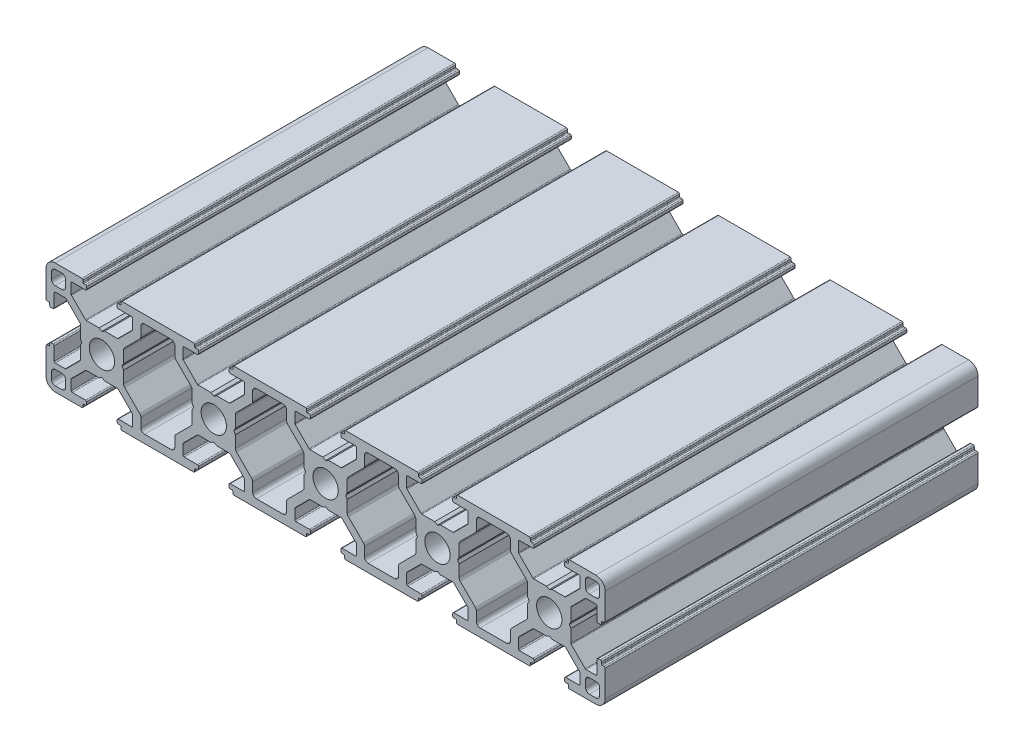
SolidWorks part; units mm, degrees
ref_plane "前视基准面" through (0, 0, 0) normal (0, 0, 1) x (1, 0, 0)
ref_plane "上视基准面" through (0, 0, 0) normal (0, 1, 0) x (1, 0, 0)
ref_plane "右视基准面" through (0, 0, 0) normal (1, 0, 0) x (0, 0, -1)
sketch "草图1" plane through (0, 0, 0) normal (0, 0, 1) x (1, 0, 0)
  line B0 (25.8114, -5.8) -> (29.25, -5.8)
  line B1 (29.25, -5.8) -> (30, -5.367)
  line B2 (30, -5.367) -> (30.75, -5.8)
  line B3 (30.75, -5.8) -> (34.1886, -5.8)
  line B4 (34.4007, -5.8879) -> (38.1622, -9.651)
  line B5 (38.25, -9.8631) -> (38.25, -12.5)
  line B6 (37.95, -12.8) -> (34.4, -12.8)
  line B7 (34.1, -13.1) -> (34.1, -13.7)
  line B8 (34.4, -14) -> (34.9, -14)
  line B9 (35.1, -14.2) -> (35.1, -14.7)
  line B10 (35.4, -15) -> (54.6, -15)
  line B11 (54.9, -14.7) -> (54.9, -14.2)
  line B12 (55.1, -14) -> (55.6, -14)
  line B13 (55.9, -13.7) -> (55.9, -13.1)
  line B14 (55.6, -12.8) -> (52.05, -12.8)
  line B15 (51.75, -12.5) -> (51.75, -9.8631)
  line B16 (51.8378, -9.651) -> (55.5993, -5.8879)
  line B17 (55.8114, -5.8) -> (59.25, -5.8)
  line B18 (59.25, -5.8) -> (60, -5.367)
  line B19 (60, -5.367) -> (60.75, -5.8)
  line B20 (60.75, -5.8) -> (64.1886, -5.8)
  line B21 (64.4007, -5.8879) -> (68.1622, -9.651)
  line B22 (68.25, -9.8631) -> (68.25, -12.5)
  line B23 (67.95, -12.8) -> (64.4, -12.8)
  line B24 (64.1, -13.1) -> (64.1, -13.7)
  line B25 (64.4, -14) -> (64.9, -14)
  line B26 (65.1, -14.2) -> (65.1, -14.7)
  line B27 (65.4, -15) -> (84.6, -15)
  line B28 (84.9, -14.7) -> (84.9, -14.2)
  line B29 (85.1, -14) -> (85.6, -14)
  line B30 (85.9, -13.7) -> (85.9, -13.1)
  line B31 (85.6, -12.8) -> (82.05, -12.8)
  line B32 (81.75, -12.5) -> (81.75, -9.8631)
  line B33 (81.8378, -9.651) -> (85.5993, -5.8879)
  line B34 (85.8114, -5.8) -> (89.25, -5.8)
  line B35 (89.25, -5.8) -> (90, -5.367)
  line B36 (90, -5.367) -> (90.75, -5.8)
  line B37 (90.75, -5.8) -> (94.1886, -5.8)
  line B38 (94.4007, -5.8879) -> (98.1622, -9.651)
  line B39 (98.25, -9.8631) -> (98.25, -12.5)
  line B40 (97.95, -12.8) -> (94.4, -12.8)
  line B41 (94.1, -13.1) -> (94.1, -13.7)
  line B42 (94.4, -14) -> (94.9, -14)
  line B43 (95.1, -14.2) -> (95.1, -14.7)
  line B44 (95.4, -15) -> (114.6, -15)
  line B45 (114.9, -14.7) -> (114.9, -14.2)
  line B46 (115.1, -14) -> (115.6, -14)
  line B47 (115.9, -13.7) -> (115.9, -13.1)
  line B48 (115.6, -12.8) -> (112.05, -12.8)
  line B49 (111.75, -12.5) -> (111.75, -9.8631)
  line B50 (111.8378, -9.651) -> (115.5993, -5.8879)
  line B51 (115.8114, -5.8) -> (119.25, -5.8)
  line B52 (119.25, -5.8) -> (120, -5.367)
  line B53 (120, -5.367) -> (120.75, -5.8)
  line B54 (120.75, -5.8) -> (124.1886, -5.8)
  line B55 (124.4007, -5.8879) -> (128.1622, -9.651)
  line B56 (128.25, -9.8631) -> (128.25, -12.5)
  line B57 (127.95, -12.8) -> (124.4, -12.8)
  line B58 (124.1, -13.1) -> (124.1, -13.7)
  line B59 (124.4, -14) -> (124.9, -14)
  line B60 (125.1, -14.2) -> (125.1, -14.7)
  line B61 (125.4, -15) -> (132.5, -15)
  line B62 (135, -12.5) -> (135, -5.4)
  line B63 (134.7, -5.1) -> (134.2, -5.1)
  line B64 (134, -4.9) -> (134, -4.4)
  line B65 (133.7, -4.1) -> (133.1, -4.1)
  line B66 (132.8, -4.4) -> (132.8, -7.95)
  line B67 (132.5, -8.25) -> (129.8553, -8.25)
  line B68 (129.6431, -8.1621) -> (125.8878, -4.4051)
  line B69 (125.8, -4.1931) -> (125.8, -0.75)
  line B70 (125.8, -0.75) -> (125.367, 0)
  line B71 (125.367, 0) -> (125.8, 0.75)
  line B72 (125.8, 0.75) -> (125.8, 4.1931)
  line B73 (125.8878, 4.4051) -> (129.6431, 8.1621)
  line B74 (129.8553, 8.25) -> (132.5, 8.25)
  line B75 (132.8, 7.95) -> (132.8, 4.4)
  line B76 (133.1, 4.1) -> (133.7, 4.1)
  line B77 (134, 4.4) -> (134, 4.9)
  line B78 (134.2, 5.1) -> (134.7, 5.1)
  line B79 (135, 5.4) -> (135, 12.5)
  line B80 (132.5, 15) -> (125.4, 15)
  line B81 (125.1, 14.7) -> (125.1, 14.2)
  line B82 (124.9, 14) -> (124.4, 14)
  line B83 (124.1, 13.7) -> (124.1, 13.1)
  line B84 (124.4, 12.8) -> (127.95, 12.8)
  line B85 (128.25, 12.5) -> (128.25, 9.8631)
  line B86 (128.1622, 9.651) -> (124.4007, 5.8879)
  line B87 (124.1886, 5.8) -> (120.75, 5.8)
  line B88 (120.75, 5.8) -> (120, 5.367)
  line B89 (120, 5.367) -> (119.25, 5.8)
  line B90 (119.25, 5.8) -> (115.8114, 5.8)
  line B91 (115.5993, 5.8879) -> (111.8378, 9.651)
  line B92 (111.75, 9.8631) -> (111.75, 12.5)
  line B93 (112.05, 12.8) -> (115.6, 12.8)
  line B94 (115.9, 13.1) -> (115.9, 13.7)
  line B95 (115.6, 14) -> (115.1, 14)
  line B96 (114.9, 14.2) -> (114.9, 14.7)
  line B97 (114.6, 15) -> (95.4, 15)
  line B98 (95.1, 14.7) -> (95.1, 14.2)
  line B99 (94.9, 14) -> (94.4, 14)
  line B100 (94.1, 13.7) -> (94.1, 13.1)
  line B101 (94.4, 12.8) -> (97.95, 12.8)
  line B102 (98.25, 12.5) -> (98.25, 9.8631)
  line B103 (98.1622, 9.651) -> (94.4007, 5.8879)
  line B104 (94.1886, 5.8) -> (90.75, 5.8)
  line B105 (90.75, 5.8) -> (90, 5.367)
  line B106 (90, 5.367) -> (89.25, 5.8)
  line B107 (89.25, 5.8) -> (85.8114, 5.8)
  line B108 (85.5993, 5.8879) -> (81.8378, 9.651)
  line B109 (81.75, 9.8631) -> (81.75, 12.5)
  line B110 (82.05, 12.8) -> (85.6, 12.8)
  line B111 (85.9, 13.1) -> (85.9, 13.7)
  line B112 (85.6, 14) -> (85.1, 14)
  line B113 (84.9, 14.2) -> (84.9, 14.7)
  line B114 (84.6, 15) -> (65.4, 15)
  line B115 (65.1, 14.7) -> (65.1, 14.2)
  line B116 (64.9, 14) -> (64.4, 14)
  line B117 (64.1, 13.7) -> (64.1, 13.1)
  line B118 (64.4, 12.8) -> (67.95, 12.8)
  line B119 (68.25, 12.5) -> (68.25, 9.8631)
  line B120 (68.1622, 9.651) -> (64.4007, 5.8879)
  line B121 (64.1886, 5.8) -> (60.75, 5.8)
  line B122 (60.75, 5.8) -> (60, 5.367)
  line B123 (60, 5.367) -> (59.25, 5.8)
  line B124 (59.25, 5.8) -> (55.8114, 5.8)
  line B125 (55.5993, 5.8879) -> (51.8378, 9.651)
  line B126 (51.75, 9.8631) -> (51.75, 12.5)
  line B127 (52.05, 12.8) -> (55.6, 12.8)
  line B128 (55.9, 13.1) -> (55.9, 13.7)
  line B129 (55.6, 14) -> (55.1, 14)
  line B130 (54.9, 14.2) -> (54.9, 14.7)
  line B131 (54.6, 15) -> (35.4, 15)
  line B132 (35.1, 14.7) -> (35.1, 14.2)
  line B133 (34.9, 14) -> (34.4, 14)
  line B134 (34.1, 13.7) -> (34.1, 13.1)
  line B135 (34.4, 12.8) -> (37.95, 12.8)
  line B136 (38.25, 12.5) -> (38.25, 9.8631)
  line B137 (38.1622, 9.651) -> (34.4007, 5.8879)
  line B138 (34.1886, 5.8) -> (30.75, 5.8)
  line B139 (30.75, 5.8) -> (30, 5.367)
  line B140 (30, 5.367) -> (29.25, 5.8)
  line B141 (29.25, 5.8) -> (25.8114, 5.8)
  line B142 (25.5993, 5.8879) -> (21.8378, 9.651)
  line B143 (21.75, 9.8631) -> (21.75, 12.5)
  line B144 (22.05, 12.8) -> (25.6, 12.8)
  line B145 (25.9, 13.1) -> (25.9, 13.7)
  line B146 (25.6, 14) -> (25.1, 14)
  line B147 (24.9, 14.2) -> (24.9, 14.7)
  line B148 (24.6, 15) -> (5.4, 15)
  line B149 (5.1, 14.7) -> (5.1, 14.2)
  line B150 (4.9, 14) -> (4.4, 14)
  line B151 (4.1, 13.7) -> (4.1, 13.1)
  line B152 (4.4, 12.8) -> (7.95, 12.8)
  line B153 (8.25, 12.5) -> (8.25, 9.8631)
  line B154 (8.1622, 9.651) -> (4.4007, 5.8879)
  line B155 (4.1886, 5.8) -> (0.75, 5.8)
  line B156 (0.75, 5.8) -> (0, 5.367)
  line B157 (0, 5.367) -> (-0.75, 5.8)
  line B158 (-0.75, 5.8) -> (-4.1886, 5.8)
  line B159 (-4.4007, 5.8879) -> (-8.1622, 9.651)
  line B160 (-8.25, 9.8631) -> (-8.25, 12.5)
  line B161 (-7.95, 12.8) -> (-4.4, 12.8)
  line B162 (-4.1, 13.1) -> (-4.1, 13.7)
  line B163 (-4.4, 14) -> (-4.9, 14)
  line B164 (-5.1, 14.2) -> (-5.1, 14.7)
  line B165 (-5.4, 15) -> (-12.5, 15)
  line B166 (-15, 12.5) -> (-15, 5.4)
  line B167 (-14.7, 5.1) -> (-14.2, 5.1)
  line B168 (-14, 4.9) -> (-14, 4.4)
  line B169 (-13.7, 4.1) -> (-13.1, 4.1)
  line B170 (-12.8, 4.4) -> (-12.8, 7.95)
  line B171 (-12.5, 8.25) -> (-9.8553, 8.25)
  line B172 (-9.6431, 8.1621) -> (-5.8878, 4.4051)
  line B173 (-5.8, 4.1931) -> (-5.8, 0.75)
  line B174 (-5.8, 0.75) -> (-5.367, 0)
  line B175 (-5.367, 0) -> (-5.8, -0.75)
  line B176 (-5.8, -0.75) -> (-5.8, -4.1931)
  line B177 (-5.8878, -4.4051) -> (-9.6431, -8.1621)
  line B178 (-9.8553, -8.25) -> (-12.5, -8.25)
  line B179 (-12.8, -7.95) -> (-12.8, -4.4)
  line B180 (-13.1, -4.1) -> (-13.7, -4.1)
  line B181 (-14, -4.4) -> (-14, -4.9)
  line B182 (-14.2, -5.1) -> (-14.7, -5.1)
  line B183 (-15, -5.4) -> (-15, -12.5)
  line B184 (-12.5, -15) -> (-5.4, -15)
  line B185 (-5.1, -14.7) -> (-5.1, -14.2)
  line B186 (-4.9, -14) -> (-4.4, -14)
  line B187 (-4.1, -13.7) -> (-4.1, -13.1)
  line B188 (-4.4, -12.8) -> (-7.95, -12.8)
  line B189 (-8.25, -12.5) -> (-8.25, -9.8631)
  line B190 (-8.1622, -9.651) -> (-4.4007, -5.8879)
  line B191 (-4.1886, -5.8) -> (-0.75, -5.8)
  line B192 (-0.75, -5.8) -> (0, -5.367)
  line B193 (0, -5.367) -> (0.75, -5.8)
  line B194 (0.75, -5.8) -> (4.1886, -5.8)
  line B195 (4.4007, -5.8879) -> (8.1622, -9.651)
  line B196 (8.25, -9.8631) -> (8.25, -12.5)
  line B197 (7.95, -12.8) -> (4.4, -12.8)
  line B198 (4.1, -13.1) -> (4.1, -13.7)
  line B199 (4.4, -14) -> (4.9, -14)
  line B200 (5.1, -14.2) -> (5.1, -14.7)
  line B201 (5.4, -15) -> (24.6, -15)
  line B202 (24.9, -14.7) -> (24.9, -14.2)
  line B203 (25.1, -14) -> (25.6, -14)
  line B204 (25.9, -13.7) -> (25.9, -13.1)
  line B205 (25.6, -12.8) -> (22.05, -12.8)
  line B206 (21.75, -12.5) -> (21.75, -9.8631)
  line B207 (21.8378, -9.651) -> (25.5993, -5.8879)
  line B208 (133.525, 10.725) -> (133.525, 12.525)
  line B209 (132.525, 13.525) -> (130.725, 13.525)
  line B210 (129.725, 12.525) -> (129.725, 10.725)
  line B211 (130.725, 9.725) -> (132.525, 9.725)
  line B212 (65.8, 3.9032) -> (65.8, 0.75)
  line B213 (65.8, 0.75) -> (65.367, 0)
  line B214 (65.367, 0) -> (65.8, -0.75)
  line B215 (65.8, -0.75) -> (65.8, -3.9032)
  line B216 (66.0927, -4.6101) -> (70.1573, -8.6764)
  line B217 (70.45, -9.3834) -> (70.45, -11.8)
  line B218 (71.45, -12.8) -> (78.55, -12.8)
  line B219 (79.55, -11.8) -> (79.55, -9.3834)
  line B220 (79.8427, -8.6764) -> (83.9073, -4.6101)
  line B221 (84.2, -3.9032) -> (84.2, -0.75)
  line B222 (84.2, -0.75) -> (84.633, 0)
  line B223 (84.633, 0) -> (84.2, 0.75)
  line B224 (84.2, 0.75) -> (84.2, 3.9032)
  line B225 (83.9073, 4.6101) -> (79.8427, 8.6764)
  line B226 (79.55, 9.3834) -> (79.55, 11.8)
  line B227 (78.55, 12.8) -> (71.45, 12.8)
  line B228 (70.45, 11.8) -> (70.45, 9.3834)
  line B229 (70.1573, 8.6764) -> (66.0927, 4.6101)
  line B230 (-12.525, 9.725) -> (-10.725, 9.725)
  line B231 (-9.725, 10.725) -> (-9.725, 12.525)
  line B232 (-10.725, 13.525) -> (-12.525, 13.525)
  line B233 (-13.525, 12.525) -> (-13.525, 10.725)
  line B234 (-13.525, -10.725) -> (-13.525, -12.525)
  line B235 (-12.525, -13.525) -> (-10.725, -13.525)
  line B236 (-9.725, -12.525) -> (-9.725, -10.725)
  line B237 (-10.725, -9.725) -> (-12.525, -9.725)
  line B238 (5.8, 3.9032) -> (5.8, 0.75)
  line B239 (5.8, 0.75) -> (5.367, 0)
  line B240 (5.367, 0) -> (5.8, -0.75)
  line B241 (5.8, -0.75) -> (5.8, -3.9032)
  line B242 (6.0927, -4.6101) -> (10.1573, -8.6764)
  line B243 (10.45, -9.3834) -> (10.45, -11.8)
  line B244 (11.45, -12.8) -> (18.55, -12.8)
  line B245 (19.55, -11.8) -> (19.55, -9.3834)
  line B246 (19.8427, -8.6764) -> (23.9073, -4.6101)
  line B247 (24.2, -3.9032) -> (24.2, -0.75)
  line B248 (24.2, -0.75) -> (24.633, 0)
  line B249 (24.633, 0) -> (24.2, 0.75)
  line B250 (24.2, 0.75) -> (24.2, 3.9032)
  line B251 (23.9073, 4.6101) -> (19.8427, 8.6764)
  line B252 (19.55, 9.3834) -> (19.55, 11.8)
  line B253 (18.55, 12.8) -> (11.45, 12.8)
  line B254 (10.45, 11.8) -> (10.45, 9.3834)
  line B255 (10.1573, 8.6764) -> (6.0927, 4.6101)
  line B256 (35.8, 3.9032) -> (35.8, 0.75)
  line B257 (35.8, 0.75) -> (35.367, 0)
  line B258 (35.367, 0) -> (35.8, -0.75)
  line B259 (35.8, -0.75) -> (35.8, -3.9032)
  line B260 (36.0927, -4.6101) -> (40.1573, -8.6764)
  line B261 (40.45, -9.3834) -> (40.45, -11.8)
  line B262 (41.45, -12.8) -> (48.55, -12.8)
  line B263 (49.55, -11.8) -> (49.55, -9.3834)
  line B264 (49.8427, -8.6764) -> (53.9073, -4.6101)
  line B265 (54.2, -3.9032) -> (54.2, -0.75)
  line B266 (54.2, -0.75) -> (54.633, 0)
  line B267 (54.633, 0) -> (54.2, 0.75)
  line B268 (54.2, 0.75) -> (54.2, 3.9032)
  line B269 (53.9073, 4.6101) -> (49.8427, 8.6764)
  line B270 (49.55, 9.3834) -> (49.55, 11.8)
  line B271 (48.55, 12.8) -> (41.45, 12.8)
  line B272 (40.45, 11.8) -> (40.45, 9.3834)
  line B273 (40.1573, 8.6764) -> (36.0927, 4.6101)
  line B274 (114.2, 0.75) -> (114.2, 3.9032)
  line B275 (113.9073, 4.6101) -> (109.8427, 8.6764)
  line B276 (109.55, 9.3834) -> (109.55, 11.8)
  line B277 (108.55, 12.8) -> (101.45, 12.8)
  line B278 (100.45, 11.8) -> (100.45, 9.3834)
  line B279 (100.1573, 8.6764) -> (96.0927, 4.6101)
  line B280 (95.8, 3.9032) -> (95.8, 0.75)
  line B281 (95.8, 0.75) -> (95.367, 0)
  line B282 (95.367, 0) -> (95.8, -0.75)
  line B283 (95.8, -0.75) -> (95.8, -3.9032)
  line B284 (96.0927, -4.6101) -> (100.1573, -8.6764)
  line B285 (100.45, -9.3834) -> (100.45, -11.8)
  line B286 (101.45, -12.8) -> (108.55, -12.8)
  line B287 (109.55, -11.8) -> (109.55, -9.3834)
  line B288 (109.8427, -8.6764) -> (113.9073, -4.6101)
  line B289 (114.2, -3.9032) -> (114.2, -0.75)
  line B290 (114.2, -0.75) -> (114.633, 0)
  line B291 (114.633, 0) -> (114.2, 0.75)
  line B292 (132.525, -9.725) -> (130.725, -9.725)
  line B293 (129.725, -10.725) -> (129.725, -12.525)
  line B294 (130.725, -13.525) -> (132.525, -13.525)
  line B295 (133.525, -12.525) -> (133.525, -10.725)
  arc B296 (34.4007, -5.8879) -> (34.1886, -5.8) centre (34.1886, -6.1) ccw
  arc B297 (38.25, -9.8631) -> (38.1622, -9.651) centre (37.95, -9.8631) ccw
  arc B298 (37.95, -12.8) -> (38.25, -12.5) centre (37.95, -12.5) ccw
  arc B299 (34.4, -12.8) -> (34.1, -13.1) centre (34.4, -13.1) ccw
  arc B300 (34.1, -13.7) -> (34.4, -14) centre (34.4, -13.7) ccw
  arc B301 (35.1, -14.2) -> (34.9, -14) centre (34.9, -14.2) ccw
  arc B302 (35.1, -14.7) -> (35.4, -15) centre (35.4, -14.7) ccw
  arc B303 (54.6, -15) -> (54.9, -14.7) centre (54.6, -14.7) ccw
  arc B304 (55.1, -14) -> (54.9, -14.2) centre (55.1, -14.2) ccw
  arc B305 (55.6, -14) -> (55.9, -13.7) centre (55.6, -13.7) ccw
  arc B306 (55.9, -13.1) -> (55.6, -12.8) centre (55.6, -13.1) ccw
  arc B307 (51.75, -12.5) -> (52.05, -12.8) centre (52.05, -12.5) ccw
  arc B308 (51.8378, -9.651) -> (51.75, -9.8631) centre (52.05, -9.8631) ccw
  arc B309 (55.8114, -5.8) -> (55.5993, -5.8879) centre (55.8114, -6.1) ccw
  arc B310 (64.4007, -5.8879) -> (64.1886, -5.8) centre (64.1886, -6.1) ccw
  arc B311 (68.25, -9.8631) -> (68.1622, -9.651) centre (67.95, -9.8631) ccw
  arc B312 (67.95, -12.8) -> (68.25, -12.5) centre (67.95, -12.5) ccw
  arc B313 (64.4, -12.8) -> (64.1, -13.1) centre (64.4, -13.1) ccw
  arc B314 (64.1, -13.7) -> (64.4, -14) centre (64.4, -13.7) ccw
  arc B315 (65.1, -14.2) -> (64.9, -14) centre (64.9, -14.2) ccw
  arc B316 (65.1, -14.7) -> (65.4, -15) centre (65.4, -14.7) ccw
  arc B317 (84.6, -15) -> (84.9, -14.7) centre (84.6, -14.7) ccw
  arc B318 (85.1, -14) -> (84.9, -14.2) centre (85.1, -14.2) ccw
  arc B319 (85.6, -14) -> (85.9, -13.7) centre (85.6, -13.7) ccw
  arc B320 (85.9, -13.1) -> (85.6, -12.8) centre (85.6, -13.1) ccw
  arc B321 (81.75, -12.5) -> (82.05, -12.8) centre (82.05, -12.5) ccw
  arc B322 (81.8378, -9.651) -> (81.75, -9.8631) centre (82.05, -9.8631) ccw
  arc B323 (85.8114, -5.8) -> (85.5993, -5.8879) centre (85.8114, -6.1) ccw
  arc B324 (94.4007, -5.8879) -> (94.1886, -5.8) centre (94.1886, -6.1) ccw
  arc B325 (98.25, -9.8631) -> (98.1622, -9.651) centre (97.95, -9.8631) ccw
  arc B326 (97.95, -12.8) -> (98.25, -12.5) centre (97.95, -12.5) ccw
  arc B327 (94.4, -12.8) -> (94.1, -13.1) centre (94.4, -13.1) ccw
  arc B328 (94.1, -13.7) -> (94.4, -14) centre (94.4, -13.7) ccw
  arc B329 (95.1, -14.2) -> (94.9, -14) centre (94.9, -14.2) ccw
  arc B330 (95.1, -14.7) -> (95.4, -15) centre (95.4, -14.7) ccw
  arc B331 (114.6, -15) -> (114.9, -14.7) centre (114.6, -14.7) ccw
  arc B332 (115.1, -14) -> (114.9, -14.2) centre (115.1, -14.2) ccw
  arc B333 (115.6, -14) -> (115.9, -13.7) centre (115.6, -13.7) ccw
  arc B334 (115.9, -13.1) -> (115.6, -12.8) centre (115.6, -13.1) ccw
  arc B335 (111.75, -12.5) -> (112.05, -12.8) centre (112.05, -12.5) ccw
  arc B336 (111.8378, -9.651) -> (111.75, -9.8631) centre (112.05, -9.8631) ccw
  arc B337 (115.8114, -5.8) -> (115.5993, -5.8879) centre (115.8114, -6.1) ccw
  arc B338 (124.4007, -5.8879) -> (124.1886, -5.8) centre (124.1886, -6.1) ccw
  arc B339 (128.25, -9.8631) -> (128.1622, -9.651) centre (127.95, -9.8631) ccw
  arc B340 (127.95, -12.8) -> (128.25, -12.5) centre (127.95, -12.5) ccw
  arc B341 (124.4, -12.8) -> (124.1, -13.1) centre (124.4, -13.1) ccw
  arc B342 (124.1, -13.7) -> (124.4, -14) centre (124.4, -13.7) ccw
  arc B343 (125.1, -14.2) -> (124.9, -14) centre (124.9, -14.2) ccw
  arc B344 (125.1, -14.7) -> (125.4, -15) centre (125.4, -14.7) ccw
  arc B345 (132.5, -15) -> (135, -12.5) centre (132.5, -12.5) ccw
  arc B346 (135, -5.4) -> (134.7, -5.1) centre (134.7, -5.4) ccw
  arc B347 (134, -4.9) -> (134.2, -5.1) centre (134.2, -4.9) ccw
  arc B348 (134, -4.4) -> (133.7, -4.1) centre (133.7, -4.4) ccw
  arc B349 (133.1, -4.1) -> (132.8, -4.4) centre (133.1, -4.4) ccw
  arc B350 (132.5, -8.25) -> (132.8, -7.95) centre (132.5, -7.95) ccw
  arc B351 (129.6431, -8.1621) -> (129.8553, -8.25) centre (129.8553, -7.95) ccw
  arc B352 (125.8, -4.1931) -> (125.8878, -4.4051) centre (126.1, -4.1931) ccw
  arc B353 (125.8878, 4.4051) -> (125.8, 4.1931) centre (126.1, 4.1931) ccw
  arc B354 (129.8553, 8.25) -> (129.6431, 8.1621) centre (129.8553, 7.95) ccw
  arc B355 (132.8, 7.95) -> (132.5, 8.25) centre (132.5, 7.95) ccw
  arc B356 (132.8, 4.4) -> (133.1, 4.1) centre (133.1, 4.4) ccw
  arc B357 (133.7, 4.1) -> (134, 4.4) centre (133.7, 4.4) ccw
  arc B358 (134.2, 5.1) -> (134, 4.9) centre (134.2, 4.9) ccw
  arc B359 (134.7, 5.1) -> (135, 5.4) centre (134.7, 5.4) ccw
  arc B360 (135, 12.5) -> (132.5, 15) centre (132.5, 12.5) ccw
  arc B361 (125.4, 15) -> (125.1, 14.7) centre (125.4, 14.7) ccw
  arc B362 (124.9, 14) -> (125.1, 14.2) centre (124.9, 14.2) ccw
  arc B363 (124.4, 14) -> (124.1, 13.7) centre (124.4, 13.7) ccw
  arc B364 (124.1, 13.1) -> (124.4, 12.8) centre (124.4, 13.1) ccw
  arc B365 (128.25, 12.5) -> (127.95, 12.8) centre (127.95, 12.5) ccw
  arc B366 (128.1622, 9.651) -> (128.25, 9.8631) centre (127.95, 9.8631) ccw
  arc B367 (124.1886, 5.8) -> (124.4007, 5.8879) centre (124.1886, 6.1) ccw
  arc B368 (115.5993, 5.8879) -> (115.8114, 5.8) centre (115.8114, 6.1) ccw
  arc B369 (111.75, 9.8631) -> (111.8378, 9.651) centre (112.05, 9.8631) ccw
  arc B370 (112.05, 12.8) -> (111.75, 12.5) centre (112.05, 12.5) ccw
  arc B371 (115.6, 12.8) -> (115.9, 13.1) centre (115.6, 13.1) ccw
  arc B372 (115.9, 13.7) -> (115.6, 14) centre (115.6, 13.7) ccw
  arc B373 (114.9, 14.2) -> (115.1, 14) centre (115.1, 14.2) ccw
  arc B374 (114.9, 14.7) -> (114.6, 15) centre (114.6, 14.7) ccw
  arc B375 (95.4, 15) -> (95.1, 14.7) centre (95.4, 14.7) ccw
  arc B376 (94.9, 14) -> (95.1, 14.2) centre (94.9, 14.2) ccw
  arc B377 (94.4, 14) -> (94.1, 13.7) centre (94.4, 13.7) ccw
  arc B378 (94.1, 13.1) -> (94.4, 12.8) centre (94.4, 13.1) ccw
  arc B379 (98.25, 12.5) -> (97.95, 12.8) centre (97.95, 12.5) ccw
  arc B380 (98.1622, 9.651) -> (98.25, 9.8631) centre (97.95, 9.8631) ccw
  arc B381 (94.1886, 5.8) -> (94.4007, 5.8879) centre (94.1886, 6.1) ccw
  arc B382 (85.5993, 5.8879) -> (85.8114, 5.8) centre (85.8114, 6.1) ccw
  arc B383 (81.75, 9.8631) -> (81.8378, 9.651) centre (82.05, 9.8631) ccw
  arc B384 (82.05, 12.8) -> (81.75, 12.5) centre (82.05, 12.5) ccw
  arc B385 (85.6, 12.8) -> (85.9, 13.1) centre (85.6, 13.1) ccw
  arc B386 (85.9, 13.7) -> (85.6, 14) centre (85.6, 13.7) ccw
  arc B387 (84.9, 14.2) -> (85.1, 14) centre (85.1, 14.2) ccw
  arc B388 (84.9, 14.7) -> (84.6, 15) centre (84.6, 14.7) ccw
  arc B389 (65.4, 15) -> (65.1, 14.7) centre (65.4, 14.7) ccw
  arc B390 (64.9, 14) -> (65.1, 14.2) centre (64.9, 14.2) ccw
  arc B391 (64.4, 14) -> (64.1, 13.7) centre (64.4, 13.7) ccw
  arc B392 (64.1, 13.1) -> (64.4, 12.8) centre (64.4, 13.1) ccw
  arc B393 (68.25, 12.5) -> (67.95, 12.8) centre (67.95, 12.5) ccw
  arc B394 (68.1622, 9.651) -> (68.25, 9.8631) centre (67.95, 9.8631) ccw
  arc B395 (64.1886, 5.8) -> (64.4007, 5.8879) centre (64.1886, 6.1) ccw
  arc B396 (55.5993, 5.8879) -> (55.8114, 5.8) centre (55.8114, 6.1) ccw
  arc B397 (51.75, 9.8631) -> (51.8378, 9.651) centre (52.05, 9.8631) ccw
  arc B398 (52.05, 12.8) -> (51.75, 12.5) centre (52.05, 12.5) ccw
  arc B399 (55.6, 12.8) -> (55.9, 13.1) centre (55.6, 13.1) ccw
  arc B400 (55.9, 13.7) -> (55.6, 14) centre (55.6, 13.7) ccw
  arc B401 (54.9, 14.2) -> (55.1, 14) centre (55.1, 14.2) ccw
  arc B402 (54.9, 14.7) -> (54.6, 15) centre (54.6, 14.7) ccw
  arc B403 (35.4, 15) -> (35.1, 14.7) centre (35.4, 14.7) ccw
  arc B404 (34.9, 14) -> (35.1, 14.2) centre (34.9, 14.2) ccw
  arc B405 (34.4, 14) -> (34.1, 13.7) centre (34.4, 13.7) ccw
  arc B406 (34.1, 13.1) -> (34.4, 12.8) centre (34.4, 13.1) ccw
  arc B407 (38.25, 12.5) -> (37.95, 12.8) centre (37.95, 12.5) ccw
  arc B408 (38.1622, 9.651) -> (38.25, 9.8631) centre (37.95, 9.8631) ccw
  arc B409 (34.1886, 5.8) -> (34.4007, 5.8879) centre (34.1886, 6.1) ccw
  arc B410 (25.5993, 5.8879) -> (25.8114, 5.8) centre (25.8114, 6.1) ccw
  arc B411 (21.75, 9.8631) -> (21.8378, 9.651) centre (22.05, 9.8631) ccw
  arc B412 (22.05, 12.8) -> (21.75, 12.5) centre (22.05, 12.5) ccw
  arc B413 (25.6, 12.8) -> (25.9, 13.1) centre (25.6, 13.1) ccw
  arc B414 (25.9, 13.7) -> (25.6, 14) centre (25.6, 13.7) ccw
  arc B415 (24.9, 14.2) -> (25.1, 14) centre (25.1, 14.2) ccw
  arc B416 (24.9, 14.7) -> (24.6, 15) centre (24.6, 14.7) ccw
  arc B417 (5.4, 15) -> (5.1, 14.7) centre (5.4, 14.7) ccw
  arc B418 (4.9, 14) -> (5.1, 14.2) centre (4.9, 14.2) ccw
  arc B419 (4.4, 14) -> (4.1, 13.7) centre (4.4, 13.7) ccw
  arc B420 (4.1, 13.1) -> (4.4, 12.8) centre (4.4, 13.1) ccw
  arc B421 (8.25, 12.5) -> (7.95, 12.8) centre (7.95, 12.5) ccw
  arc B422 (8.1622, 9.651) -> (8.25, 9.8631) centre (7.95, 9.8631) ccw
  arc B423 (4.1886, 5.8) -> (4.4007, 5.8879) centre (4.1886, 6.1) ccw
  arc B424 (-4.4007, 5.8879) -> (-4.1886, 5.8) centre (-4.1886, 6.1) ccw
  arc B425 (-8.25, 9.8631) -> (-8.1622, 9.651) centre (-7.95, 9.8631) ccw
  arc B426 (-7.95, 12.8) -> (-8.25, 12.5) centre (-7.95, 12.5) ccw
  arc B427 (-4.4, 12.8) -> (-4.1, 13.1) centre (-4.4, 13.1) ccw
  arc B428 (-4.1, 13.7) -> (-4.4, 14) centre (-4.4, 13.7) ccw
  arc B429 (-5.1, 14.2) -> (-4.9, 14) centre (-4.9, 14.2) ccw
  arc B430 (-5.1, 14.7) -> (-5.4, 15) centre (-5.4, 14.7) ccw
  arc B431 (-12.5, 15) -> (-15, 12.5) centre (-12.5, 12.5) ccw
  arc B432 (-15, 5.4) -> (-14.7, 5.1) centre (-14.7, 5.4) ccw
  arc B433 (-14, 4.9) -> (-14.2, 5.1) centre (-14.2, 4.9) ccw
  arc B434 (-14, 4.4) -> (-13.7, 4.1) centre (-13.7, 4.4) ccw
  arc B435 (-13.1, 4.1) -> (-12.8, 4.4) centre (-13.1, 4.4) ccw
  arc B436 (-12.5, 8.25) -> (-12.8, 7.95) centre (-12.5, 7.95) ccw
  arc B437 (-9.6431, 8.1621) -> (-9.8553, 8.25) centre (-9.8553, 7.95) ccw
  arc B438 (-5.8, 4.1931) -> (-5.8878, 4.4051) centre (-6.1, 4.1931) ccw
  arc B439 (-5.8878, -4.4051) -> (-5.8, -4.1931) centre (-6.1, -4.1931) ccw
  arc B440 (-9.8553, -8.25) -> (-9.6431, -8.1621) centre (-9.8553, -7.95) ccw
  arc B441 (-12.8, -7.95) -> (-12.5, -8.25) centre (-12.5, -7.95) ccw
  arc B442 (-12.8, -4.4) -> (-13.1, -4.1) centre (-13.1, -4.4) ccw
  arc B443 (-13.7, -4.1) -> (-14, -4.4) centre (-13.7, -4.4) ccw
  arc B444 (-14.2, -5.1) -> (-14, -4.9) centre (-14.2, -4.9) ccw
  arc B445 (-14.7, -5.1) -> (-15, -5.4) centre (-14.7, -5.4) ccw
  arc B446 (-15, -12.5) -> (-12.5, -15) centre (-12.5, -12.5) ccw
  arc B447 (-5.4, -15) -> (-5.1, -14.7) centre (-5.4, -14.7) ccw
  arc B448 (-4.9, -14) -> (-5.1, -14.2) centre (-4.9, -14.2) ccw
  arc B449 (-4.4, -14) -> (-4.1, -13.7) centre (-4.4, -13.7) ccw
  arc B450 (-4.1, -13.1) -> (-4.4, -12.8) centre (-4.4, -13.1) ccw
  arc B451 (-8.25, -12.5) -> (-7.95, -12.8) centre (-7.95, -12.5) ccw
  arc B452 (-8.1622, -9.651) -> (-8.25, -9.8631) centre (-7.95, -9.8631) ccw
  arc B453 (-4.1886, -5.8) -> (-4.4007, -5.8879) centre (-4.1886, -6.1) ccw
  arc B454 (4.4007, -5.8879) -> (4.1886, -5.8) centre (4.1886, -6.1) ccw
  arc B455 (8.25, -9.8631) -> (8.1622, -9.651) centre (7.95, -9.8631) ccw
  arc B456 (7.95, -12.8) -> (8.25, -12.5) centre (7.95, -12.5) ccw
  arc B457 (4.4, -12.8) -> (4.1, -13.1) centre (4.4, -13.1) ccw
  arc B458 (4.1, -13.7) -> (4.4, -14) centre (4.4, -13.7) ccw
  arc B459 (5.1, -14.2) -> (4.9, -14) centre (4.9, -14.2) ccw
  arc B460 (5.1, -14.7) -> (5.4, -15) centre (5.4, -14.7) ccw
  arc B461 (24.6, -15) -> (24.9, -14.7) centre (24.6, -14.7) ccw
  arc B462 (25.1, -14) -> (24.9, -14.2) centre (25.1, -14.2) ccw
  arc B463 (25.6, -14) -> (25.9, -13.7) centre (25.6, -13.7) ccw
  arc B464 (25.9, -13.1) -> (25.6, -12.8) centre (25.6, -13.1) ccw
  arc B465 (21.75, -12.5) -> (22.05, -12.8) centre (22.05, -12.5) ccw
  arc B466 (21.8378, -9.651) -> (21.75, -9.8631) centre (22.05, -9.8631) ccw
  arc B467 (25.8114, -5.8) -> (25.5993, -5.8879) centre (25.8114, -6.1) ccw
  arc B468 (132.525, 9.725) -> (133.525, 10.725) centre (132.525, 10.725) ccw
  arc B469 (133.525, 12.525) -> (132.525, 13.525) centre (132.525, 12.525) ccw
  arc B470 (130.725, 13.525) -> (129.725, 12.525) centre (130.725, 12.525) ccw
  arc B471 (129.725, 10.725) -> (130.725, 9.725) centre (130.725, 10.725) ccw
  arc B472 (65.8, -3.9032) -> (66.0927, -4.6101) centre (66.8, -3.9032) ccw
  arc B473 (70.45, -9.3834) -> (70.1573, -8.6764) centre (69.45, -9.3834) ccw
  arc B474 (70.45, -11.8) -> (71.45, -12.8) centre (71.45, -11.8) ccw
  arc B475 (78.55, -12.8) -> (79.55, -11.8) centre (78.55, -11.8) ccw
  arc B476 (79.8427, -8.6764) -> (79.55, -9.3834) centre (80.55, -9.3834) ccw
  arc B477 (83.9073, -4.6101) -> (84.2, -3.9032) centre (83.2, -3.9032) ccw
  arc B478 (84.2, 3.9032) -> (83.9073, 4.6101) centre (83.2, 3.9032) ccw
  arc B479 (79.55, 9.3834) -> (79.8427, 8.6764) centre (80.55, 9.3834) ccw
  arc B480 (79.55, 11.8) -> (78.55, 12.8) centre (78.55, 11.8) ccw
  arc B481 (71.45, 12.8) -> (70.45, 11.8) centre (71.45, 11.8) ccw
  arc B482 (70.1573, 8.6764) -> (70.45, 9.3834) centre (69.45, 9.3834) ccw
  arc B483 (66.0927, 4.6101) -> (65.8, 3.9032) centre (66.8, 3.9032) ccw
  arc B484 (-13.525, 10.725) -> (-12.525, 9.725) centre (-12.525, 10.725) ccw
  arc B485 (-10.725, 9.725) -> (-9.725, 10.725) centre (-10.725, 10.725) ccw
  arc B486 (-9.725, 12.525) -> (-10.725, 13.525) centre (-10.725, 12.525) ccw
  arc B487 (-12.525, 13.525) -> (-13.525, 12.525) centre (-12.525, 12.525) ccw
  arc B488 (-12.525, -9.725) -> (-13.525, -10.725) centre (-12.525, -10.725) ccw
  arc B489 (-13.525, -12.525) -> (-12.525, -13.525) centre (-12.525, -12.525) ccw
  arc B490 (-10.725, -13.525) -> (-9.725, -12.525) centre (-10.725, -12.525) ccw
  arc B491 (-9.725, -10.725) -> (-10.725, -9.725) centre (-10.725, -10.725) ccw
  arc B492 (5.8, -3.9032) -> (6.0927, -4.6101) centre (6.8, -3.9032) ccw
  arc B493 (10.45, -9.3834) -> (10.1573, -8.6764) centre (9.45, -9.3834) ccw
  arc B494 (10.45, -11.8) -> (11.45, -12.8) centre (11.45, -11.8) ccw
  arc B495 (18.55, -12.8) -> (19.55, -11.8) centre (18.55, -11.8) ccw
  arc B496 (19.8427, -8.6764) -> (19.55, -9.3834) centre (20.55, -9.3834) ccw
  arc B497 (23.9073, -4.6101) -> (24.2, -3.9032) centre (23.2, -3.9032) ccw
  arc B498 (24.2, 3.9032) -> (23.9073, 4.6101) centre (23.2, 3.9032) ccw
  arc B499 (19.55, 9.3834) -> (19.8427, 8.6764) centre (20.55, 9.3834) ccw
  arc B500 (19.55, 11.8) -> (18.55, 12.8) centre (18.55, 11.8) ccw
  arc B501 (11.45, 12.8) -> (10.45, 11.8) centre (11.45, 11.8) ccw
  arc B502 (10.1573, 8.6764) -> (10.45, 9.3834) centre (9.45, 9.3834) ccw
  arc B503 (6.0927, 4.6101) -> (5.8, 3.9032) centre (6.8, 3.9032) ccw
  arc B504 (35.8, -3.9032) -> (36.0927, -4.6101) centre (36.8, -3.9032) ccw
  arc B505 (40.45, -9.3834) -> (40.1573, -8.6764) centre (39.45, -9.3834) ccw
  arc B506 (40.45, -11.8) -> (41.45, -12.8) centre (41.45, -11.8) ccw
  arc B507 (48.55, -12.8) -> (49.55, -11.8) centre (48.55, -11.8) ccw
  arc B508 (49.8427, -8.6764) -> (49.55, -9.3834) centre (50.55, -9.3834) ccw
  arc B509 (53.9073, -4.6101) -> (54.2, -3.9032) centre (53.2, -3.9032) ccw
  arc B510 (54.2, 3.9032) -> (53.9073, 4.6101) centre (53.2, 3.9032) ccw
  arc B511 (49.55, 9.3834) -> (49.8427, 8.6764) centre (50.55, 9.3834) ccw
  arc B512 (49.55, 11.8) -> (48.55, 12.8) centre (48.55, 11.8) ccw
  arc B513 (41.45, 12.8) -> (40.45, 11.8) centre (41.45, 11.8) ccw
  arc B514 (40.1573, 8.6764) -> (40.45, 9.3834) centre (39.45, 9.3834) ccw
  arc B515 (36.0927, 4.6101) -> (35.8, 3.9032) centre (36.8, 3.9032) ccw
  arc B516 (114.2, 3.9032) -> (113.9073, 4.6101) centre (113.2, 3.9032) ccw
  arc B517 (109.55, 9.3834) -> (109.8427, 8.6764) centre (110.55, 9.3834) ccw
  arc B518 (109.55, 11.8) -> (108.55, 12.8) centre (108.55, 11.8) ccw
  arc B519 (101.45, 12.8) -> (100.45, 11.8) centre (101.45, 11.8) ccw
  arc B520 (100.1573, 8.6764) -> (100.45, 9.3834) centre (99.45, 9.3834) ccw
  arc B521 (96.0927, 4.6101) -> (95.8, 3.9032) centre (96.8, 3.9032) ccw
  arc B522 (95.8, -3.9032) -> (96.0927, -4.6101) centre (96.8, -3.9032) ccw
  arc B523 (100.45, -9.3834) -> (100.1573, -8.6764) centre (99.45, -9.3834) ccw
  arc B524 (100.45, -11.8) -> (101.45, -12.8) centre (101.45, -11.8) ccw
  arc B525 (108.55, -12.8) -> (109.55, -11.8) centre (108.55, -11.8) ccw
  arc B526 (109.8427, -8.6764) -> (109.55, -9.3834) centre (110.55, -9.3834) ccw
  arc B527 (113.9073, -4.6101) -> (114.2, -3.9032) centre (113.2, -3.9032) ccw
  arc B528 (133.525, -10.725) -> (132.525, -9.725) centre (132.525, -10.725) ccw
  arc B529 (130.725, -9.725) -> (129.725, -10.725) centre (130.725, -10.725) ccw
  arc B530 (129.725, -12.525) -> (130.725, -13.525) centre (130.725, -12.525) ccw
  arc B531 (132.525, -13.525) -> (133.525, -12.525) centre (132.525, -12.525) ccw
  circle B532 centre (120, 0) radius 3.4
  circle B533 centre (90, 0) radius 3.4
  circle B534 centre (30, 0) radius 3.4
  circle B535 centre (0, 0) radius 3.4
  circle B536 centre (60, 0) radius 3.4
sketch_block_instance "A$C0C1372D9-1"
sketch_block "A$C0C1372D9"
extrude "凸台-拉伸1" add sketch "草图1" along normal blind 100
